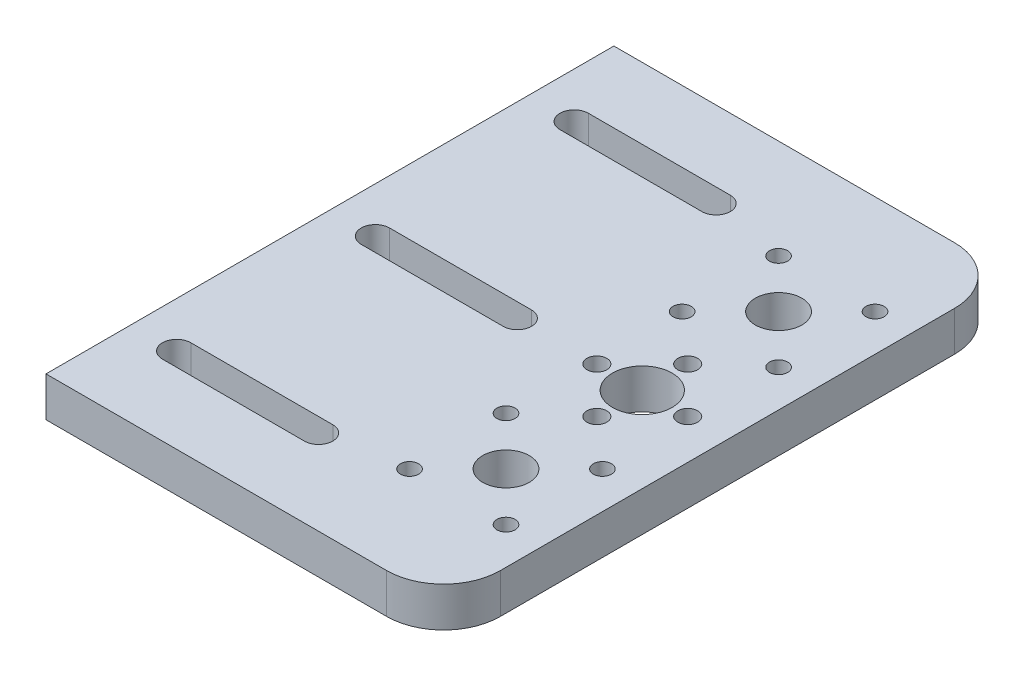
SolidWorks part; units mm, degrees
ref_plane "Front Plane" through (0, 0, 0) normal (0, 0, 1) x (1, 0, 0)
ref_plane "Top Plane" through (0, 0, 0) normal (0, 1, 0) x (1, 0, 0)
ref_plane "Right Plane" through (0, 0, 0) normal (1, 0, 0) x (0, 0, -1)
sketch "Sketch1" plane through (0, 0, 0) normal (0, 1, 0) x (1, 0, 0)
  line L0 (49.75, 50) -> (60.25, 50) construction
  line L1 (0, 0) -> (70, 0)
  line L2 (0, 0) -> (0, 100)
  line L3 (0, 100) -> (70, 100)
  line L4 (70, 0) -> (70, 100)
  line L5 (42, 74) -> (68, 74) construction
  line L9 (8, 85) -> (33, 85) construction
  line L10 (8, 87.5) -> (33, 87.5)
  line L11 (8, 82.5) -> (33, 82.5)
  line L12 (56, 0) -> (72, 0)
  line L14 (8, 50) -> (33, 50) construction
  line L15 (8, 52.5) -> (33, 52.5)
  line L16 (8, 47.5) -> (33, 47.5)
  line L20 (5.5, 50) -> (35.5, 50) construction
  line L25 (55, 45.85) -> (55, 55.25) construction
  line L26 (68, 61) -> (42, 61) construction
  line L27 (68, 61) -> (68, 87) construction
  line L28 (68, 87) -> (42, 87) construction
  line L29 (42, 61) -> (42, 87) construction
  line L30 (68, 61) -> (42, 87) construction
  line L31 (68, 87) -> (42, 61) construction
  line L32 (68, 13) -> (42, 39) construction
  line L33 (68, 39) -> (42, 13) construction
  line L34 (42, 39) -> (42, 13) construction
  line L35 (68, 13) -> (42, 13) construction
  line L36 (68, 39) -> (68, 13) construction
  line L37 (68, 39) -> (42, 39) construction
  line L38 (42, 26) -> (68, 26) construction
  line L39 (8, 15) -> (33, 15) construction
  line L40 (8, 12.5) -> (33, 12.5)
  line L41 (8, 17.5) -> (33, 17.5)
  circle A0 centre (55, 50) radius 5.25
  circle A1 centre (55, 74) radius 4.1
  arc A7 (8, 87.5) -> (8, 82.5) centre (8, 85) ccw
  arc A8 (33, 82.5) -> (33, 87.5) centre (33, 85) ccw
  arc A9 (8, 52.5) -> (8, 47.5) centre (8, 50) ccw
  arc A10 (33, 47.5) -> (33, 52.5) centre (33, 50) ccw
  circle A20 centre (55, 50) radius 8 construction
  circle A21 centre (47, 50) radius 1.75
  circle A22 centre (55, 58) radius 1.75
  circle A23 centre (63, 50) radius 1.75
  circle A24 centre (55, 42) radius 1.75
  circle A25 centre (63.49, 82.49) radius 1.6
  circle A26 centre (46.51, 65.51) radius 1.6
  circle A27 centre (46.51, 82.49) radius 1.6
  circle A28 centre (63.49, 65.51) radius 1.6
  circle A29 centre (63.49, 34.49) radius 1.6
  circle A30 centre (46.51, 17.51) radius 1.6
  circle A31 centre (46.51, 34.49) radius 1.6
  circle A32 centre (63.49, 17.51) radius 1.6
  circle A33 centre (55, 26) radius 4.1
  arc A34 (8, 12.5) -> (8, 17.5) centre (8, 15) cw
  arc A35 (33, 17.5) -> (33, 12.5) centre (33, 15) cw
  point P8 (143, 50)
  point P14 (55, 50.55)
  point P16 (55, 50)
  point P21 (20.5, 85)
  point P30 (20.5, 50)
  point P40 (20.5, 50)
  point P42 (20.5, 15)
  point P45 (55, 50)
  point P46 (143, 50)
  point P47 (0, 50)
  point P56 (55, 50)
  point P66 (55, 74)
  point P83 (55, 26)
  dimension "D4" = 10.5
  dimension "D5" = 8.2
  dimension "D6" = 16
  dimension "D9" = 2.5
  dimension "D8" = 3.5
  dimension "D16" = 3.2
  dimension "D1" = 70
  dimension "D2" = 100
  dimension "D3" = 50
  dimension "D7" = 24
  dimension "D10" = 15
  dimension "D11" = 8
  dimension "D12" = 25
  dimension "D13" = 15
  dimension "D14" = 4
  dimension "D15" = 26
  dimension "D17" = 4.51
extrude "Boss-Extrude1" add sketch "Sketch1" along normal blind 7
fillet "Fillet1" radius 10 2 edges at (70, 3.5, 0) (70, 3.5, -100)
